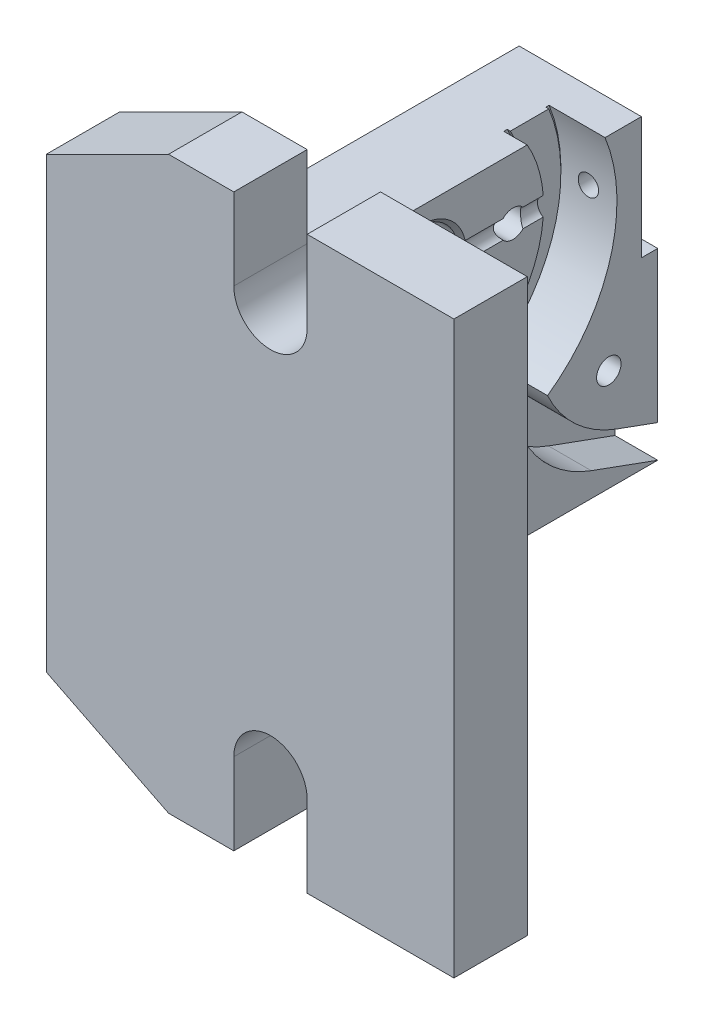
SolidWorks part; units mm, degrees
ref_plane "Спереди" through (0, 0, 0) normal (0, 0, 1) x (1, 0, 0)
ref_plane "Сверху" through (0, 0, 0) normal (0, 1, 0) x (1, 0, 0)
ref_plane "Справа" through (0, 0, 0) normal (1, 0, 0) x (0, 0, -1)
ref_plane "Плоскость4" through (29.9994, 0, 0) normal (1, 0, 0) x (0, 0, -1)
sketch "Эскиз1" plane through (29.9994, 0, 0) normal (1, 0, 0) x (0, 0, -1)
  line L0 (14.9192, 90.0005) -> (0, 90.0005)
  line L1 (0, 90.0005) -> (0, 15.0005)
  line L2 (0, 15.0005) -> (102, 15.0005)
  line L3 (102, 15.0005) -> (85.6938, 20.9355)
  arc A0 (85.6938, 20.9355) -> (67.9664, 38.3248) centre (95.9544, 49.1263) cw
  arc A1 (67.9664, 38.3248) -> (14.9192, 90.0005) centre (52, 75) cw
extrude "Бобышка-Вытянуть1" add sketch "Эскиз1" against normal blind 10.5
sketch "Эскиз2" plane through (19.4994, 0, 0) normal (-1, 0, 0) x (0, 0, 1)
  line L0 (0, 15.0005) -> (-102, 15.0005)
  line L1 (-102, 15.0005) -> (-102, 90.0005)
  line L2 (-102, 90.0005) -> (0, 90.0005)
  line L3 (0, 90.0005) -> (0, 15.0005)
extrude "Бобышка-Вытянуть2" add sketch "Эскиз2" along normal blind 19.4994
sketch "Эскиз3" plane through (0, 0, 0) normal (0, 0, 1) x (1, 0, 0)
  line L0 (29.9994, 0) -> (0, 15.0005)
  line L1 (0, 15.0005) -> (0, 124.9975)
  line L2 (0, 124.9975) -> (29.9976, 140)
  line L3 (29.9976, 140) -> (29.9994, 140)
  line L4 (29.9994, 140) -> (29.9994, 0)
extrude "Бобышка-Вытянуть3" add sketch "Эскиз3" along normal blind 18
sketch "Эскиз4" plane through (29.9994, 0, 0) normal (1, 0, 0) x (0, 0, -1)
  line L0 (-18, 140) -> (0, 140)
  line L1 (0, 140) -> (0, 0)
  line L2 (0, 0) -> (-18, 0)
  line L3 (-18, 0) -> (-18, 140)
extrude "Бобышка-Вытянуть4" add sketch "Эскиз4" along normal blind 70.0006
sketch "Эскиз5" plane through (19.4994, 0, 0) normal (1, 0, 0) x (0, 0, -1)
  line L0 (89.0808, 90.0005) -> (102, 90.0005)
  line L1 (102, 90.0005) -> (102, 23.0005)
  line L2 (102, 23.0005) -> (91.9268, 26.6669)
  arc A0 (91.9268, 26.6669) -> (74.9654, 42.2496) centre (102.1874, 54.8577) cw
  arc A1 (74.9654, 42.2496) -> (89.0808, 90.0005) centre (52, 75) ccw
extrude "Бобышка-Вытянуть5" add sketch "Эскиз5" along normal blind 10.5
ref_plane "Плоскость5" through (16.2494, 0, 0) normal (-1, 0, 0) x (0, -1, 0)
sketch "Эскиз6" plane through (16.2494, 0, 0) normal (-1, 0, 0) x (0, -1, 0)
  line L0 (-90.0005, -14.9192) -> (-90.0005, -89.0808)
  arc A0 (-90.0005, -89.0808) -> (-90.0005, -14.9192) centre (-75, -52) ccw
extrude "Вырез-Вытянуть1" cut sketch "Эскиз6" against normal up to next
sketch "Эскиз7" plane through (0, 0, 0) normal (-1, 0, 0) x (0, 0, 1)
  line L0 (-102, 60.0005) -> (-98, 60.0005)
  line L1 (-98, 60.0005) -> (-98, 90.0005)
  line L2 (-98, 90.0005) -> (-102, 90.0005)
  line L3 (-102, 90.0005) -> (-102, 60.0005)
extrude "Вырез-Вытянуть2" cut sketch "Эскиз7" against normal through all
sketch "Эскиз8" plane through (0, 0, 18) normal (0, 0, 1) x (1, 0, 0)
  line L0 (64, 140) -> (46, 140)
  line L1 (46, 140) -> (46, 120)
  line L2 (64, 120) -> (64, 140)
  arc A0 (46, 120) -> (64, 120) centre (55, 120) ccw
extrude "Вырез-Вытянуть3" cut sketch "Эскиз8" against normal through all
sketch "Эскиз9" plane through (0, 0, 18) normal (0, 0, 1) x (1, 0, 0)
  line L0 (46, 0) -> (64, 0)
  line L1 (64, 0) -> (64, 20)
  line L2 (46, 20) -> (46, 0)
  arc A0 (64, 20) -> (46, 20) centre (55, 20) ccw
extrude "Вырез-Вытянуть4" cut sketch "Эскиз9" against normal through all
sketch "Эскиз10" plane through (16.2494, 0, 0) normal (1, 0, 0) x (0, 0, -1)
  line L0 (15.7295, 90.0005) -> (88.2705, 90.0005)
  arc A0 (88.2705, 90.0005) -> (15.7295, 90.0005) centre (52, 75) cw
extrude "Бобышка-Вытянуть6" add sketch "Эскиз10" along normal blind 0.75
hole_wizard "Отверстие с зазором M521" positions "Эскиз12" profile "Эскиз11" hole size "M52" standard "Ansi Metric"
sketch "Эскиз12" plane through (16.9994, 0, 0) normal (1, 0, 0) x (0, 0, -1)
  point P0 (52, 75)
sketch "Эскиз11" plane through (16.9994, 75, -52) normal (0, 1, 0) x (0, 0, -1)
  line L0 (0, 0) -> (0, 16.9994)
  line L1 (0, 16.9994) -> (30.75, 16.9994)
  line L2 (30.75, 16.9994) -> (30.75, 0)
  line L5 (30.75, 0) -> (0, 0)
  line L11 (0, -6.35) -> (0, 107.95) construction
  dimension "Диаметр сквозного отверстия" = 61.5
  dimension "Глубина сквозного отверстия" = 16.9994
sketch "Эскиз13" plane through (16.2494, 0, 0) normal (-1, 0, 0) x (0, -1, 0)
  line L0 (-90.0005, -26.0196) -> (-90.0005, -77.9804)
  arc A0 (-90.0005, -77.9804) -> (-90.0005, -26.0196) centre (-75, -52) ccw
extrude "Бобышка-Вытянуть7" add sketch "Эскиз13" against normal blind 5.75
hole_wizard "Диаметр отверстия Ø6.7 (6.7)1" positions "Эскиз17" profile "Эскиз16" hole size "Ø6.7" standard "Ansi Metric"
sketch "Эскиз17" plane through (21.9994, 0, 0) normal (1, 0, 0) x (0, 0, -1)
  point P0 (74.5, 75)
  point P1 (29.5, 75)
sketch "Эскиз16" plane through (21.9994, 75, -74.5) normal (0, 1, 0) x (0, 0, -1)
  line L0 (0, 0) -> (0, 5.751)
  line L1 (0, 5.751) -> (3.35, 5.751)
  line L2 (3.35, 5.751) -> (3.35, 0)
  line L5 (3.35, 0) -> (0, 0)
  line L11 (0, -6.35) -> (0, 107.95) construction
  dimension "Диаметр сквозного отверстия" = 6.7
  dimension "Глубина сквозного отверстия" = 5.751
hole_wizard "Диаметр отверстия Ø20.0 (20)1" positions "Эскиз19" profile "Эскиз18" hole size "Ø20.0" standard "Ansi Metric"
sketch "Эскиз19" plane through (21.9994, 0, 0) normal (1, 0, 0) x (0, 0, -1)
  point P0 (52, 75)
sketch "Эскиз18" plane through (21.9994, 75, -52) normal (0, 1, 0) x (0, 0, -1)
  line L0 (0, 0) -> (0, 5.751)
  line L1 (0, 5.751) -> (10, 5.751)
  line L2 (10, 5.751) -> (10, 0)
  line L5 (10, 0) -> (0, 0)
  line L11 (0, -6.35) -> (0, 107.95) construction
  dimension "Диаметр сквозного отверстия" = 20
  dimension "Глубина сквозного отверстия" = 5.751
hole_wizard "Диаметр отверстия Ø4.0 (4)1" positions "Эскиз21" profile "Эскиз20" hole size "Ø4.0" standard "Ansi Metric"
sketch "Эскиз21" plane through (16.9994, 0, 0) normal (1, 0, 0) x (0, 0, -1)
  point P0 (17, 75)
  point P1 (52, 40)
sketch "Эскиз20" plane through (16.9994, 75, -17) normal (0, 1, 0) x (0, 0, -1)
  line L0 (0, 0) -> (0, 16.9994)
  line L1 (0, 16.9994) -> (2, 16.9994)
  line L2 (2, 16.9994) -> (2, 0)
  line L5 (2, 0) -> (0, 0)
  line L11 (0, -6.35) -> (0, 107.95) construction
  dimension "Диаметр сквозного отверстия" = 4
  dimension "Глубина сквозного отверстия" = 16.9994
hole_wizard "Диаметр отверстия Ø6.0 (6)1" positions "Эскиз23" profile "Эскиз22" hole size "Ø6.0" standard "Ansi Metric"
sketch "Эскиз23" plane through (29.9994, 0, 0) normal (1, 0, 0) x (0, 0, -1)
  point P0 (90, 40.0005)
sketch "Эскиз22" plane through (29.9994, 40.0005, -90) normal (0, 1, 0) x (0, 0, -1)
  line L0 (0, 0) -> (0, 30.0004)
  line L1 (0, 30.0004) -> (3, 30.0004)
  line L2 (3, 30.0004) -> (3, 0)
  line L5 (3, 0) -> (0, 0)
  line L11 (0, -6.35) -> (0, 107.95) construction
  dimension "Диаметр сквозного отверстия" = 6
  dimension "Глубина сквозного отверстия" = 30.0004
hole_wizard "Диаметр отверстия Ø5.0 (5)1" positions "Эскиз25" profile "Эскиз24" hole size "Ø5.0" standard "Ansi Metric"
sketch "Эскиз25" plane through (0, 0, -98) normal (0, 0, -1) x (-1, 0, 0)
  point P0 (-23, 75.0005)
sketch "Эскиз24" plane through (23, 75.0005, -98) normal (1, 0, 0) x (0, 1, 0)
  line L0 (0, 0) -> (0, 46)
  line L1 (0, 46) -> (2.5, 46)
  line L2 (2.5, 46) -> (2.5, 0)
  line L5 (2.5, 0) -> (0, 0)
  line L11 (0, -6.35) -> (0, 107.95) construction
  dimension "Диаметр сквозного отверстия" = 5
  dimension "Глубина сквозного отверстия" = 46
hole_wizard "Отверстие с зазором M61" positions "Эскиз27" profile "Эскиз26" hole size "M6" standard "Ansi Metric"
sketch "Эскиз27" plane through (0, 0, -102) normal (0, 0, -1) x (-1, 0, 0)
  point P0 (-15.8867, 33.1286)
sketch "Эскиз26" plane through (15.8867, 33.1286, -102) normal (1, 0, 0) x (0, 1, 0)
  line L0 (0, 0) -> (0, 6)
  line L1 (0, 6) -> (3.2358, 6)
  line L2 (3.2358, 6) -> (3.2358, 0)
  line L5 (3.2358, 0) -> (0, 0)
  line L10 (0, 6) -> (-3.2358, 6) construction
  line L11 (0, -6.35) -> (0, 107.95) construction
  dimension "Диаметр отверстия" = 6.4715
  dimension "Глубина отверстия" = 6
  dimension "Угол заточки сверла" = 180
chamfer "Фаска1" distance 1 angle 45 1 edges at (21.9994, 74.9994, -42)
sketch "Эскиз28" plane through (0, 0, 0) normal (-1, 0, 0) x (0, 0, 1)
  line L0 (-78.843, 90.0005) -> (-25.157, 90.0005)
  circle A0 centre (-29.5, 75) radius 3.35 construction
  circle A1 centre (-52, 75) radius 10 construction
  circle A2 centre (-74.5, 75) radius 3.35 construction
  arc A3 (-78.843, 90.0005) -> (-25.157, 90.0005) centre (-52, 75) ccw construction
  circle A4 centre (-29.5, 75) radius 3.35
  circle A5 centre (-52, 75) radius 10
  circle A6 centre (-74.5, 75) radius 3.35
  arc A7 (-78.843, 90.0005) -> (-25.157, 90.0005) centre (-52, 75) ccw
extrude "Бобышка-Вытянуть8" add sketch "Эскиз28" against normal up to vertex
sketch "Эскиз30" plane through (0, 15.0005, 0) normal (0, -1, 0) x (1, 0, 0)
  line L5 (29.9994, -102) -> (29.9994, 0)
  line L6 (29.9994, 0) -> (0, 0)
  line L7 (0, 0) -> (0, -102)
  line L8 (0, -102) -> (19.4994, -102)
  line L9 (19.4994, -102) -> (29.9994, -102)
  line L10 (29.9994, -102) -> (29.9994, 0) construction
  line L11 (29.9994, 0) -> (0, 0) construction
  line L12 (0, 0) -> (0, -102) construction
  line L13 (0, -102) -> (19.4994, -102) construction
  line L14 (19.4994, -102) -> (29.9994, -102) construction
  circle A0 centre (19.9994, -77) radius 3
  dimension "D4" = 6
  dimension "D2" = 10
  dimension "D3" = 25
  dimension "D1" = 0
extrude "Вырез-Вытянуть5" cut sketch "Эскиз30" against normal blind 7 contours A0
sketch "Эскиз32" plane through (0, 0, 0) normal (-1, 0, 0) x (0, 0, 1)
  circle A0 centre (-90, 40.0005) radius 3 construction
  circle A1 centre (-90, 40.0005) radius 3
extrude "Бобышка-Вытянуть9" add sketch "Эскиз32" against normal blind 21
